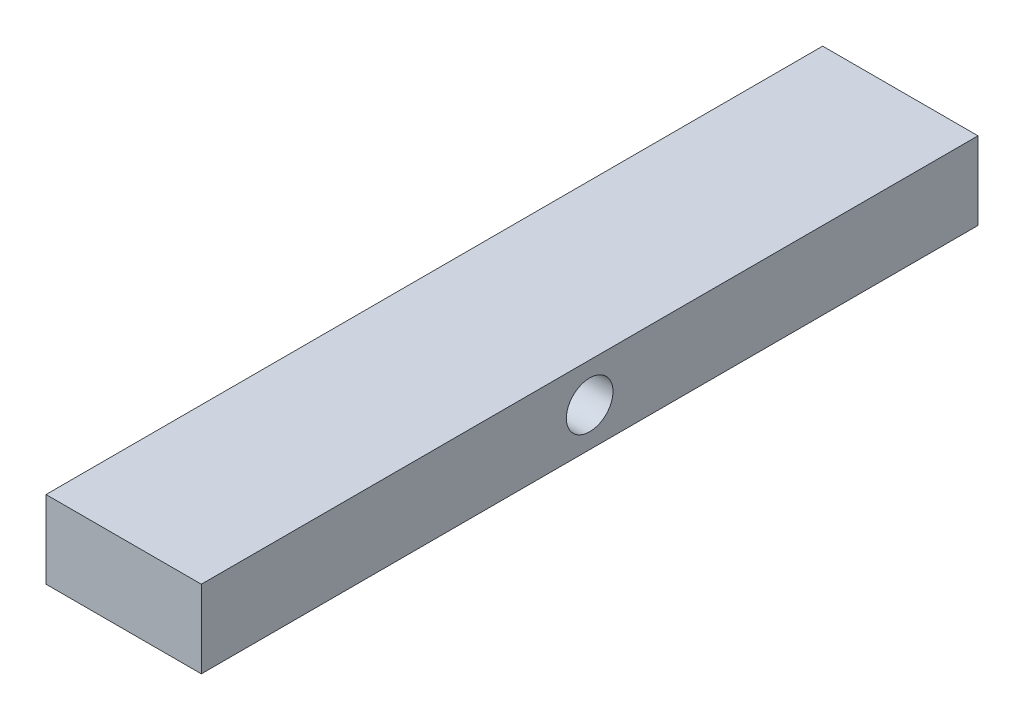
SolidWorks part; units mm, degrees
ref_plane "Front Plane" through (0, 0, 0) normal (0, 0, 1) x (1, 0, 0)
ref_plane "Top Plane" through (0, 0, 0) normal (0, 1, 0) x (1, 0, 0)
ref_plane "Right Plane" through (0, 0, 0) normal (1, 0, 0) x (0, 0, -1)
sketch "Sketch1" plane through (0, 0, 0) normal (0, 0, 1) x (1, 0, 0)
  line L1 (-50, 25) -> (50, 25)
  line L2 (-50, 25) -> (-50, -25)
  line L3 (-50, -25) -> (50, -25)
  line L4 (50, 25) -> (50, -25)
  line L5 (-50, 25) -> (50, -25) construction
  line L6 (-50, -25) -> (50, 25) construction
  point P0 (0, 0)
  dimension "D1" = 100
  dimension "D2" = 50
extrude "Boss-Extrude1" add sketch "Sketch1" along normal blind 500
sketch "Sketch2" plane through (50, 0, 0) normal (1, 0, 0) x (0, 0, -1)
  line L0 (0, -25) -> (0, 25) construction
  circle A0 centre (-250, 0) radius 15
  dimension "D1" = 30
  dimension "D2" = 250
extrude "Cut-Extrude1" cut sketch "Sketch2" against normal through all
